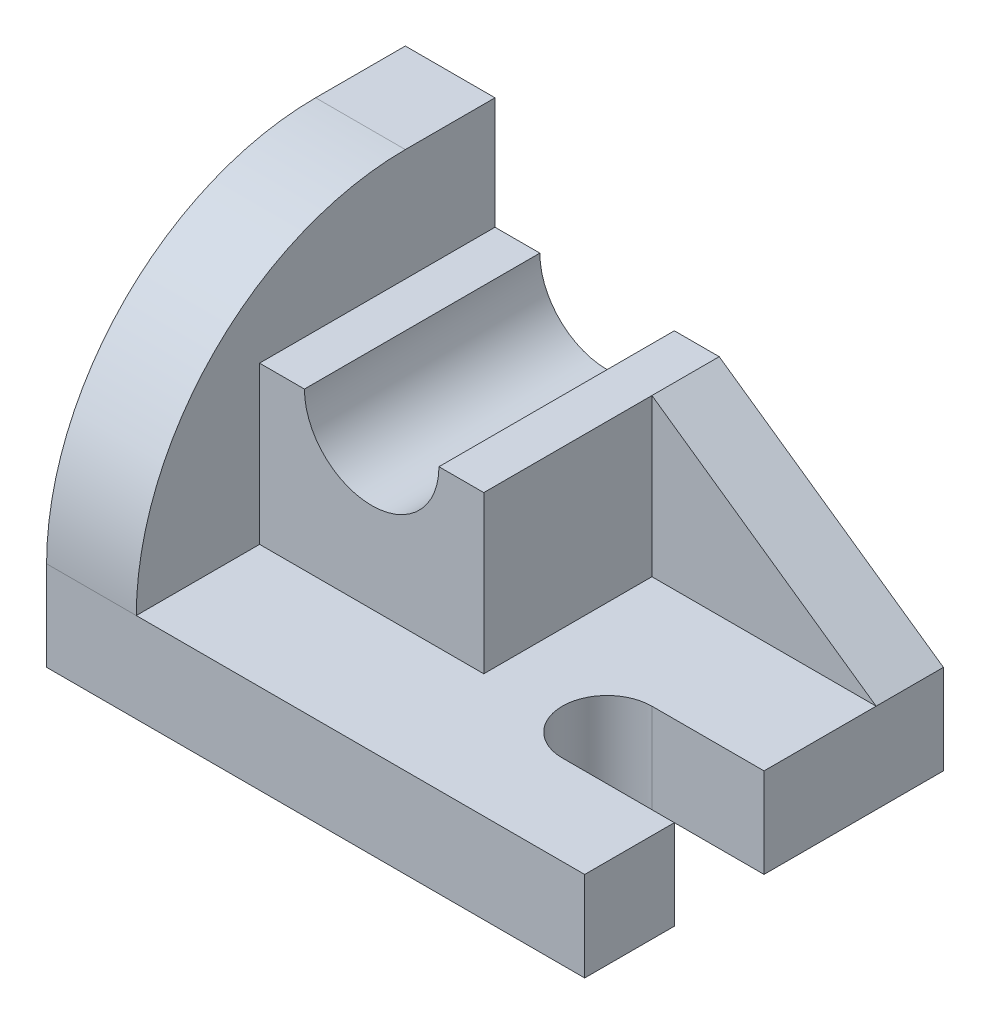
SolidWorks part; units mm, degrees
ref_plane "Front Plane" through (0, 0, 0) normal (0, 0, 1) x (1, 0, 0)
ref_plane "Top Plane" through (0, 0, 0) normal (0, 1, 0) x (1, 0, 0)
ref_plane "Right Plane" through (0, 0, 0) normal (1, 0, 0) x (0, 0, -1)
sketch "Sketch1" plane through (0, 0, 0) normal (0, 1, 0) x (1, 0, 0)
  line L0 (96, 24) -> (76, 24) construction
  line L1 (0, 0) -> (96, 0)
  line L2 (0, 0) -> (0, 64)
  line L3 (0, 64) -> (96, 64)
  line L4 (96, 0) -> (96, 16)
  line L5 (96, 16) -> (76, 16)
  line L6 (96, 32) -> (76, 32)
  line L7 (96, 32) -> (96, 64)
  arc A1 (76, 32) -> (76, 16) centre (76, 24) ccw
  point P7 (86, 24)
  point P12 (0, 0)
  dimension "D5" = 8
  dimension "D1" = 96
  dimension "D2" = 64
  dimension "D3" = 24
  dimension "D4" = 20
extrude "Boss-Extrude5" add sketch "Sketch1" along normal blind 16 contours L1 L4 L5 A1 L6 L7 L3 L2
sketch "Sketch4" plane through (0, 0, 0) normal (-1, 0, 0) x (0, 0, 1)
  line L1 (-64, 16) -> (0, 16)
  line L2 (-64, 16) -> (-64, 64)
  line L3 (-64, 64) -> (-48, 64)
  arc A0 (0, 16) -> (-48, 64) centre (-48, 16) ccw
extrude "Boss-Extrude6" add sketch "Sketch4" against normal blind 16
sketch "Sketch5" plane through (0, 0, -64) normal (0, 0, -1) x (-1, 0, 0)
  line L0 (-48, 44) -> (-56, 44)
  line L1 (-16, 16) -> (-56, 16)
  line L2 (-16, 16) -> (-16, 44)
  line L3 (-16, 44) -> (-24, 44)
  line L4 (-56, 16) -> (-56, 44)
  arc A0 (-48, 44) -> (-24, 44) centre (-36, 44) ccw
  dimension "D3" = 24
  dimension "D1" = 40
  dimension "D2" = 28
extrude "Boss-Extrude7" add sketch "Sketch5" against normal blind 42 contours L2 L3 A0 L0 L4 L1
sketch "Sketch6" plane through (0, 0, -64) normal (0, 0, -1) x (-1, 0, 0)
  line L0 (-96, 16) -> (-56, 16)
  line L1 (-56, 16) -> (-56, 44)
  line L2 (-56, 44) -> (-96, 16)
extrude "Boss-Extrude8" add sketch "Sketch6" against normal blind 12 contours L2 L0 L1
